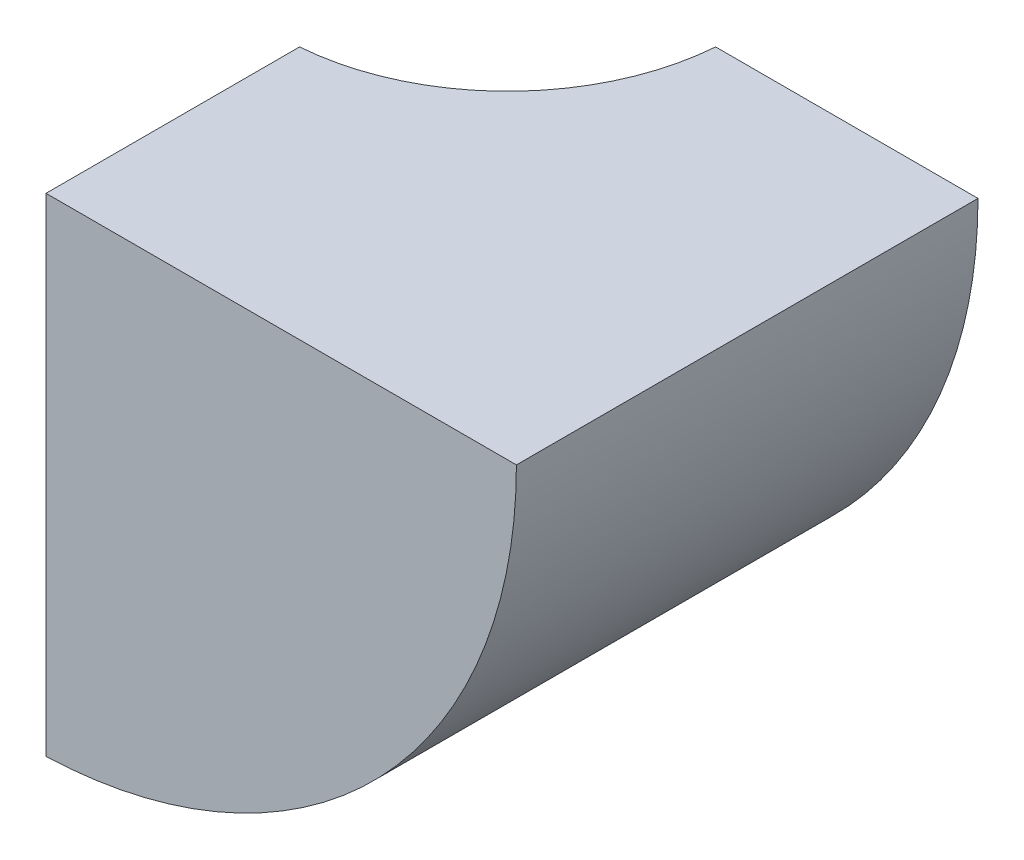
SolidWorks part; units mm, degrees
ref_plane "Front Plane" through (0, 0, 0) normal (0, 0, 1) x (1, 0, 0)
ref_plane "Top Plane" through (0, 0, 0) normal (0, 1, 0) x (1, 0, 0)
ref_plane "Right Plane" through (0, 0, 0) normal (1, 0, 0) x (0, 0, -1)
sketch "Sketch1" plane through (0, 0, 0) normal (0, 0, 1) x (1, 0, 0)
  circle A0 centre (0, 0) radius 16.6
  dimension "D1" = 33.2
extrude "Boss-Extrude1" add sketch "Sketch1" along normal blind 16.3
sketch "Sketch2" plane through (0, 0, 16.3) normal (0, 0, 1) x (1, 0, 0)
  line L0 (0, 0) -> (16.6, 0)
  line L1 (0, 0) -> (0, -16.6)
  circle A0 centre (0, 0) radius 16.6 construction
  arc A1 (16.6, 0) -> (0, -16.6) centre (0, 0) ccw
extrude "Cut-Extrude1" cut sketch "Sketch2" against normal through all
sketch "Sketch3" plane through (0, 0, 0) normal (0, 1, 0) x (1, 0, 0)
  circle A0 centre (0, 0) radius 7.7
  dimension "D1" = 15.4
extrude "Cut-Extrude2" cut sketch "Sketch3" against normal through all
sketch "Sketch4" plane through (0, 0, 0) normal (0, 1, 0) x (1, 0, 0)
  line L1 (0, -16.3) -> (0.6, -16.3)
  line L2 (0, -16.3) -> (0, -6.788)
  line L3 (0, -6.788) -> (0.6, -6.788)
  line L4 (0.6, -16.3) -> (0.6, -6.788)
  line L5 (16.6, 0) -> (6.2585, 0)
  line L6 (16.6, 0) -> (16.6, -0.6)
  line L7 (16.6, -0.6) -> (6.2585, -0.6)
  line L8 (6.2585, 0) -> (6.2585, -0.6)
  dimension "D1" = 0.6
  dimension "D2" = 0.6
extrude "Cut-Extrude3" cut sketch "Sketch4" against normal through all
